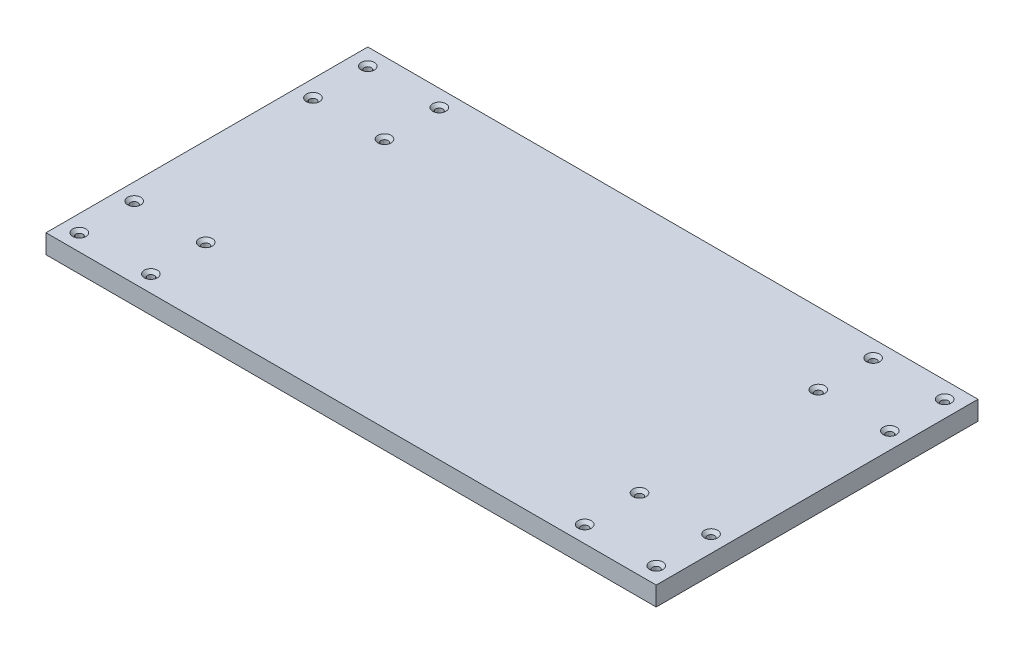
SolidWorks part; units mm, degrees
ref_plane "Front Plane" through (0, 0, 0) normal (0, 0, 1) x (1, 0, 0)
ref_plane "Top Plane" through (0, 0, 0) normal (0, 1, 0) x (1, 0, 0)
ref_plane "Right Plane" through (0, 0, 0) normal (1, 0, 0) x (0, 0, -1)
sketch "Sketch1" plane through (0, 0, 0) normal (0, 1, 0) x (1, 0, 0)
  line L1 (0, 0) -> (203.2, 0)
  line L2 (0, 0) -> (0, 107.1562)
  line L3 (0, 107.1562) -> (203.2, 107.1562)
  line L4 (203.2, 0) -> (203.2, 107.1562)
  dimension "D1" = 203.2
  dimension "D2" = 107.1562
extrude "Boss-Extrude1" add sketch "Sketch1" along normal blind 6.35
hole_wizard "CSK for M2 Flat Head Machine Screw1" positions "Sketch2" profile "Sketch3" countersink size "M2" standard "ANSI Metric" end condition through all
sketch "Sketch2" plane through (0, 6.35, 0) normal (0, 1, 0) x (1, 0, 0)
  line L0 (0, 101.6) -> (203.2, 101.6)
  line L1 (0, 107.1562) -> (0, 0) construction
  line L2 (203.2, 0) -> (203.2, 107.1562) construction
  line L5 (5.5562, 0) -> (5.5563, 107.1562)
  line L6 (0, 0) -> (203.2, 0) construction
  line L7 (203.2, 107.1562) -> (0, 107.1562) construction
  line L10 (29.3687, 107.1562) -> (29.3688, 0)
  line L13 (0, 5.5562) -> (203.2, 5.5562)
  line L16 (197.6437, 0) -> (197.6437, 107.1562)
  line L19 (173.8312, 0) -> (173.8312, 107.1562)
  line L21 (0, 83.3438) -> (203.2, 83.3438)
  line L24 (0, 23.8125) -> (203.2, 23.8125)
  point P0 (5.5562, 101.6)
  point P40 (1.2015, 116.4001)
  point P42 (1.2015, 113.37)
  point P45 (29.3687, 101.6)
  point P47 (5.5563, 5.5562)
  point P49 (29.3688, 5.5562)
  point P51 (173.8312, 5.5562)
  point P53 (173.8312, 101.6)
  point P55 (197.6437, 101.6)
  point P57 (197.6437, 5.5562)
  point P67 (5.5563, 83.3438)
  point P69 (29.3688, 83.3438)
  point P71 (5.5563, 23.8125)
  point P72 (173.8312, 83.3438)
  point P74 (197.6437, 83.3438)
  point P76 (173.8312, 23.8125)
  point P78 (197.6437, 23.8125)
  point P80 (29.3688, 23.8125)
  dimension "D1" = 5.5562
  dimension "D2" = 23.8125
  dimension "D3" = 5.5562
  dimension "D4" = 5.5562
  dimension "D5" = 23.8125
  dimension "D6" = 5.5562
  dimension "D7" = 18.2562
  dimension "D8" = 18.2562
sketch "Sketch3" plane through (5.5562, 6.35, -101.6) normal (1, 0, 0) x (0, 0, 1)
  line L0 (0, 0) -> (0, 6.35)
  line L1 (0, 6.35) -> (1.2, 6.35)
  line L2 (1.2, 6.35) -> (1.2, 1)
  line L3 (1.2, 1) -> (2.2, 0)
  line L5 (2.2, 0) -> (0, 0)
  line L6 (-1.2, 1) -> (-2.2, 0) construction
  line L11 (0, -6.35) -> (0, 107.95) construction
  dimension "Thru Hole Dia." = 2.4
  dimension "Thru Hole Depth" = 6.35
  dimension "Near C'Sink Dia." = 4.4
  dimension "Near C'Sink Angle" = 90
